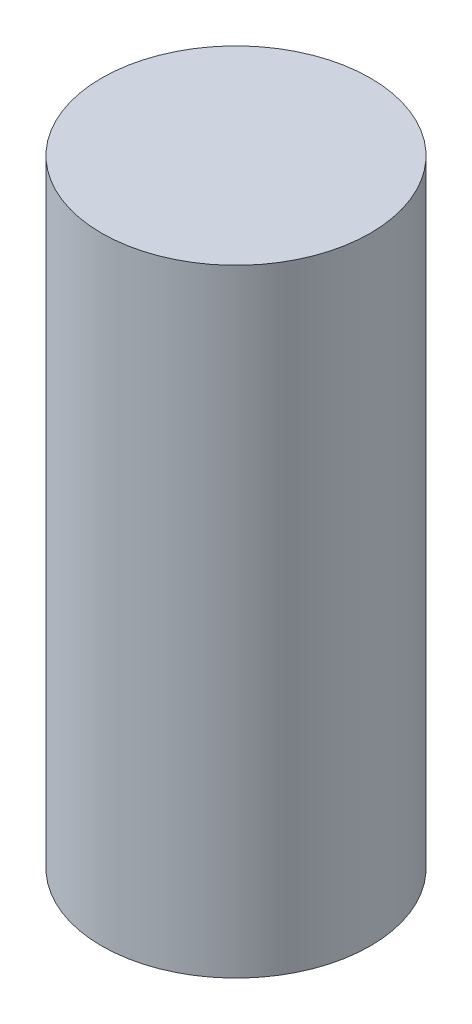
SolidWorks part; units mm, degrees
ref_plane "Front Plane" through (0, 0, 0) normal (0, 0, 1) x (1, 0, 0)
ref_plane "Top Plane" through (0, 0, 0) normal (0, 1, 0) x (1, 0, 0)
ref_plane "Right Plane" through (0, 0, 0) normal (1, 0, 0) x (0, 0, -1)
sketch "Sketch1" plane through (0, 0, 0) normal (0, 1, 0) x (1, 0, 0)
  circle A0 centre (0, 0) radius 12.3
  dimension "D1" = 24.6
extrude "Boss-Extrude1" add sketch "Sketch1" along normal blind 56.5
sketch "Sketch2" plane through (0, 0, 0) normal (0, -1, 0) x (1, 0, 0)
  circle A0 centre (0, 0) radius 10
  dimension "D1" = 20
extrude "Cut-Extrude1" cut sketch "Sketch2" against normal blind 6.5
